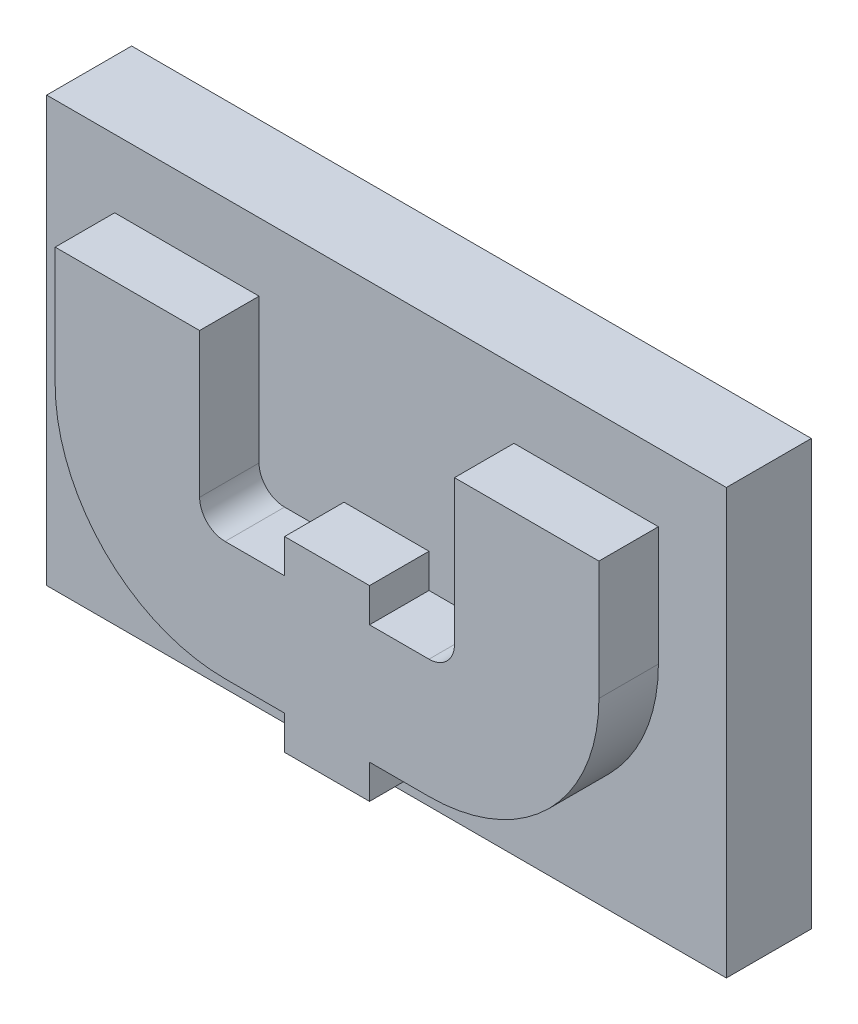
SolidWorks part; units mm, degrees
ref_plane "Front Plane" through (0, 0, 0) normal (0, 0, 1) x (1, 0, 0)
ref_plane "Top Plane" through (0, 0, 0) normal (0, 1, 0) x (1, 0, 0)
ref_plane "Right Plane" through (0, 0, 0) normal (1, 0, 0) x (0, 0, -1)
sketch "Sketch1" plane through (0, 0, 0) normal (0, 0, 1) x (1, 0, 0)
  line L1 (0, 0) -> (80, 0)
  line L2 (0, 0) -> (0, 50)
  line L3 (0, 50) -> (80, 50)
  line L4 (80, 0) -> (80, 50)
  dimension "D1" = 50
  dimension "D2" = 80
extrude "Boss-Extrude1" add sketch "Sketch1" along normal blind 10
sketch "Sketch2" plane through (0, 0, 10) normal (0, 0, 1) x (1, 0, 0)
  line L0 (80, 50) -> (0, 50) construction
  line L1 (8, 42) -> (72, 42)
  line L2 (8, 42) -> (8, 8)
  line L3 (8, 8) -> (72, 8)
  line L4 (72, 42) -> (72, 8)
  line L5 (0, 50) -> (0, 0) construction
  line L6 (80, 0) -> (80, 50) construction
  line L7 (0, 0) -> (80, 0) construction
  dimension "D1" = 8
  dimension "D2" = 8
  dimension "D3" = 8
  dimension "D4" = 8
extrude "Boss-Extrude2" add sketch "Sketch2" along normal blind 7
fillet "Fillet1" radius 20 2 edges at (72, 8, 13.5) (8, 8, 13.5)
sketch "Sketch3" plane through (0, 8, 0) normal (0, -1, 0) x (-1, 0, 0)
  line L0 (-28, -17) -> (-52, -17) construction
  line L1 (-35, -17) -> (-45, -17)
  line L2 (-35, -17) -> (-35, -10)
  line L3 (-35, -10) -> (-45, -10)
  line L4 (-45, -17) -> (-45, -10)
  line L5 (-28, -10) -> (-52, -10) construction
  line L6 (-28, -17) -> (-28, -10) construction
  line L7 (-52, -10) -> (-52, -17) construction
  dimension "D1" = 7
  dimension "D2" = 7
extrude "Boss-Extrude3" add sketch "Sketch3" along normal blind 4
sketch "Sketch4" plane through (0, 0, 17) normal (0, 0, 1) x (1, 0, 0)
  line L0 (72, 42) -> (8, 42) construction
  line L1 (25, 42) -> (55, 42)
  line L2 (25, 42) -> (25, 22)
  line L3 (25, 22) -> (55, 22)
  line L4 (55, 42) -> (55, 22)
  line L5 (8, 42) -> (8, 28) construction
  line L6 (72, 28) -> (72, 42) construction
  dimension "D1" = 17
  dimension "D2" = 17
  dimension "D3" = 20
extrude "Cut-Extrude1" cut sketch "Sketch4" against normal up to surface (7 mm away) up to face at (40, 25, 10)
fillet "Fillet2" radius 3 2 edges at (55, 22, 13.5) (25, 22, 13.5)
sketch "Sketch5" plane through (0, 22, 0) normal (0, 1, 0) x (1, 0, 0)
  line L0 (28, -17) -> (52, -17) construction
  line L1 (35, -17) -> (45, -17)
  line L2 (35, -17) -> (35, -10)
  line L3 (35, -10) -> (45, -10)
  line L4 (45, -17) -> (45, -10)
  line L5 (28, -10) -> (52, -10) construction
  line L6 (28, -10) -> (28, -17) construction
  line L7 (52, -17) -> (52, -10) construction
  dimension "D1" = 7
  dimension "D2" = 7
extrude "Boss-Extrude4" add sketch "Sketch5" along normal blind 4
